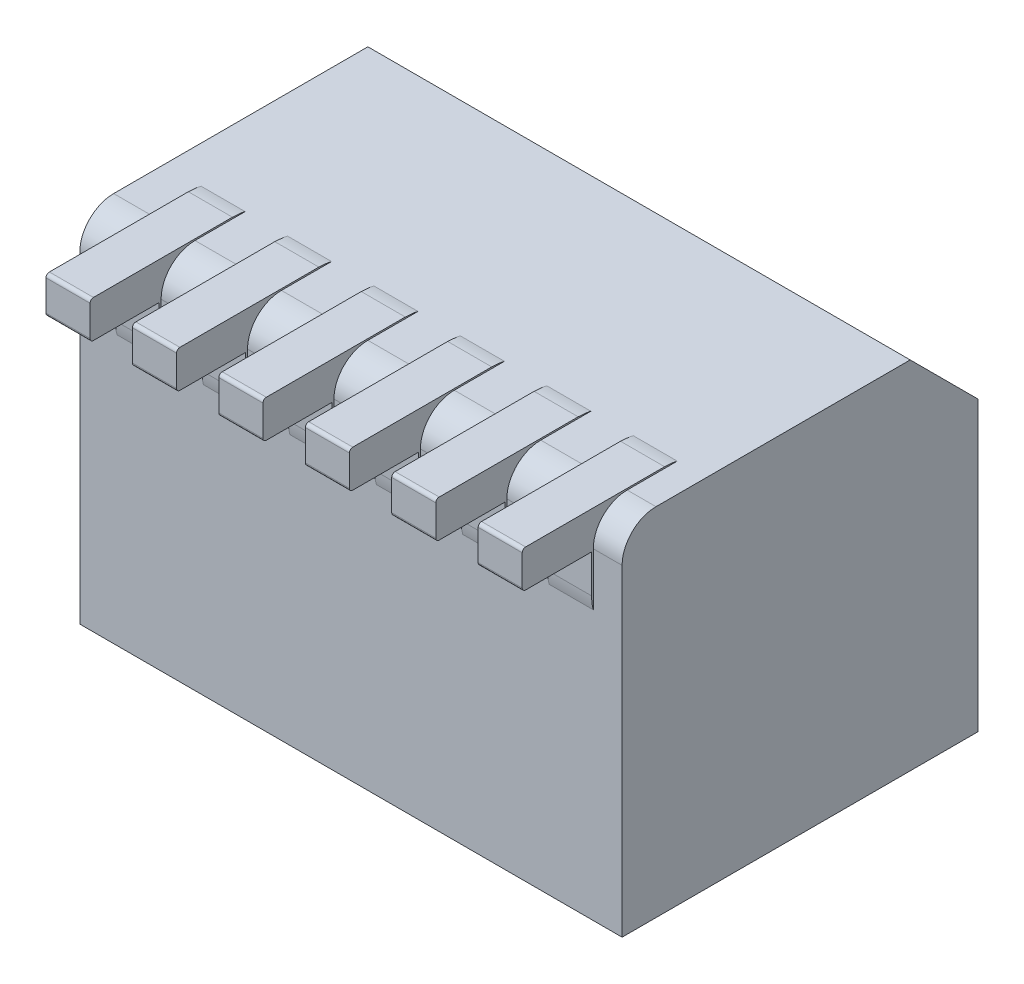
SolidWorks part; units mm, degrees
ref_plane "Front Plane" through (0, 0, 0) normal (0, 0, 1) x (1, 0, 0)
ref_plane "Top Plane" through (0, 0, 0) normal (0, 1, 0) x (1, 0, 0)
ref_plane "Right Plane" through (0, 0, 0) normal (1, 0, 0) x (0, 0, -1)
sketch "Sketch1" plane through (0, 0, 0) normal (1, 0, 0) x (0, 0, -1)
  line L0 (3.25, 5.25) -> (5.25, 3.25)
  line L1 (-4.25, 5.25) -> (3.25, 5.25)
  line L2 (-5.25, 4.25) -> (-5.25, -5.25)
  line L3 (-5.25, -5.25) -> (5.25, -5.25)
  line L4 (5.25, 3.25) -> (5.25, -5.25)
  line L5 (-5.25, 5.25) -> (5.25, -5.25) construction
  line L6 (-5.25, -5.25) -> (5.25, 5.25) construction
  arc A0 (-4.25, 5.25) -> (-5.25, 4.25) centre (-4.25, 4.25) ccw
  point P0 (0, 0)
  dimension "D3" = 1
  dimension "D1" = 10.5
  dimension "D2" = 10.5
extrude "Boss-Extrude1" add sketch "Sketch1" along normal mid plane 16
sketch "Sketch2" plane through (8, 0, 0) normal (1, 0, 0) x (0, 0, -1)
  line L1 (-3.146, 5.2947) -> (-7.246, 5.2947)
  line L3 (-5.3097, 4.1947) -> (-7.246, 4.1947)
  line L4 (-7.346, 5.1947) -> (-7.346, 4.2947)
  line L6 (-5.3076, 3.0786) -> (-5.3097, 4.1947)
  arc A0 (-5.3076, 3.0786) -> (-3.146, 5.2947) centre (-3.1867, 3.1721) ccw
  arc A1 (-7.246, 4.1947) -> (-7.346, 4.2947) centre (-7.246, 4.2947) cw
  arc A2 (-7.246, 5.2947) -> (-7.346, 5.1947) centre (-7.246, 5.1947) ccw
  point P6 (-7.281, 4.1966)
  point P7 (0, 0)
  point P15 (-7.346, 5.2947)
  dimension "D3" = 0.1
  dimension "D1" = 1.1
  dimension "D2" = 4.2
extrude "Boss-Extrude2" add sketch "Sketch2" along normal mid plane 1.3 from offset 1.5 separate body offset against normal yes
pattern_linear "LPattern1" count 6 spacing 2.55 along (-1, 0, 0) of "Boss-Extrude2"
